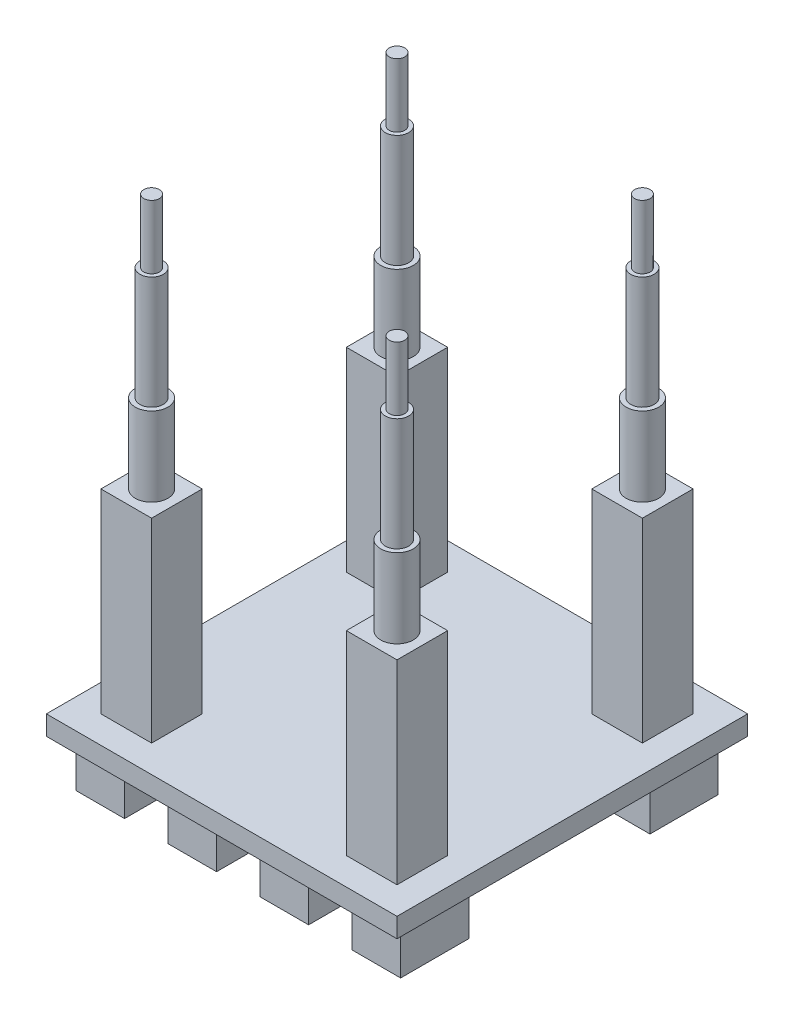
SolidWorks part; units mm, degrees
ref_plane "Front Plane" through (0, 0, 0) normal (0, 0, 1) x (1, 0, 0)
ref_plane "Top Plane" through (0, 0, 0) normal (0, 1, 0) x (1, 0, 0)
ref_plane "Right Plane" through (0, 0, 0) normal (1, 0, 0) x (0, 0, -1)
sketch "Sketch1" plane through (0, 0, 0) normal (0, 1, 0) x (1, 0, 0)
  line L1 (-22.86, 22.86) -> (22.86, 22.86)
  line L2 (-22.86, 22.86) -> (-22.86, -22.86)
  line L3 (-22.86, -22.86) -> (22.86, -22.86)
  line L4 (22.86, 22.86) -> (22.86, -22.86)
extrude "Boss-Extrude1" add sketch "Sketch1" along normal blind 2.54
sketch "Sketch2" plane through (0, 2.54, 0) normal (0, 1, 0) x (1, 0, 0)
  line L0 (0, 22.86) -> (0, -22.86) construction
  line L1 (22.86, 22.86) -> (-22.86, 22.86) construction
  line L2 (-22.86, -22.86) -> (22.86, -22.86) construction
  line L3 (-22.86, 0) -> (22.86, 0) construction
  line L4 (-22.86, 22.86) -> (-22.86, -22.86) construction
  line L5 (22.86, -22.86) -> (22.86, 22.86) construction
  line L6 (19.302, 19.302) -> (12.698, 19.302)
  line L7 (-19.302, 19.302) -> (-12.698, 19.302)
  line L8 (-19.302, 19.302) -> (-19.302, 12.698)
  line L9 (-19.302, 12.698) -> (-12.698, 12.698)
  line L10 (-12.698, 19.302) -> (-12.698, 12.698)
  line L11 (-19.302, 19.302) -> (-12.698, 12.698) construction
  line L12 (-19.302, 12.698) -> (-12.698, 19.302) construction
  line L13 (19.302, 19.302) -> (19.302, 12.698)
  line L14 (19.302, 12.698) -> (12.698, 12.698)
  line L15 (12.698, 19.302) -> (12.698, 12.698)
  line L16 (-19.302, -12.698) -> (-12.698, -12.698)
  line L17 (-19.302, -19.302) -> (-19.302, -12.698)
  line L18 (-19.302, -19.302) -> (-12.698, -19.302)
  line L19 (-12.698, -19.302) -> (-12.698, -12.698)
  line L20 (12.698, -19.302) -> (12.698, -12.698)
  line L21 (19.302, -12.698) -> (12.698, -12.698)
  line L22 (19.302, -19.302) -> (19.302, -12.698)
  line L23 (19.302, -19.302) -> (12.698, -19.302)
  point P1 (-16, 16)
  dimension "D1" = 6.604
extrude "Boss-Extrude2" add sketch "Sketch2" along normal blind 25.4
sketch "Sketch5" plane through (0, 27.94, 0) normal (0, 1, 0) x (1, 0, 0)
  line L0 (0, 22.86) -> (0, -22.86) construction
  line L2 (22.86, 0) -> (-22.86, 0) construction
  line L3 (-22.86, 0) -> (22.86, 0) construction
  line L4 (-22.86, 22.86) -> (-22.86, -22.86) construction
  line L5 (0, 22.86) -> (0, -22.86) construction
  circle A0 centre (-16, 16) radius 2.125
  circle A1 centre (16, 16) radius 2.125
  circle A2 centre (-16, -16) radius 2.125
  circle A3 centre (16, -16) radius 2.125
  dimension "D1" = 4.25
extrude "Boss-Extrude5" add sketch "Sketch5" along normal blind 10.3
sketch "Sketch8" plane through (0, 38.24, 0) normal (0, 1, 0) x (1, 0, 0)
  line L0 (-16, 0) -> (16, 0) construction
  line L1 (0, -16) -> (0, 16) construction
  circle A0 centre (16, 16) radius 1.525
  circle A1 centre (-16, 16) radius 1.525
  circle A2 centre (-16, -16) radius 1.525
  circle A3 centre (16, -16) radius 1.525
  point P6 (0, 0)
  point P10 (0, 0)
extrude "Boss-Extrude8" add sketch "Sketch8" along normal blind 14.7
sketch "Sketch9" plane through (0, 52.94, 0) normal (0, 1, 0) x (1, 0, 0)
  line L0 (-16, 0) -> (16, 0) construction
  line L1 (0, -16) -> (0, 16) construction
  circle A0 centre (16, 16) radius 1.015
  circle A1 centre (-16, 16) radius 1.015
  circle A2 centre (-16, -16) radius 1.015
  circle A3 centre (16, -16) radius 1.015
  point P7 (0, 0)
  point P11 (0, 0)
extrude "Boss-Extrude9" add sketch "Sketch9" along normal blind 8.3
sketch "Sketch7" plane through (0, 0, 0) normal (0, -1, 0) x (1, 0, 0)
  line L0 (0, 22.86) -> (0, -22.86) construction
  line L1 (-9.175, 20.701) -> (-2.825, 20.701)
  line L2 (-9.175, 20.701) -> (-9.175, 11.811)
  line L3 (-9.175, 11.811) -> (-2.825, 11.811)
  line L4 (-2.825, 20.701) -> (-2.825, 11.811)
  line L5 (-9.175, 20.701) -> (-2.825, 11.811) construction
  line L6 (-9.175, 11.811) -> (-2.825, 20.701) construction
  line L7 (-22.86, 22.86) -> (22.86, 22.86) construction
  line L8 (22.86, -22.86) -> (-22.86, -22.86) construction
  line L9 (-22.86, 0) -> (22.86, 0) construction
  line L10 (-22.86, -22.86) -> (-22.86, 22.86) construction
  line L11 (22.86, 22.86) -> (22.86, -22.86) construction
  line L16 (-6, 16.256) -> (0, 16.256) construction
  line L17 (-6, 16.256) -> (-12, 16.256) construction
  line L18 (-12, 22.86) -> (-12, -22.86) construction
  line L19 (-14.825, 11.811) -> (-21.175, 11.811)
  line L20 (-21.175, 20.701) -> (-21.175, 11.811)
  line L21 (-14.825, 20.701) -> (-14.825, 11.811)
  line L22 (-14.825, 20.701) -> (-21.175, 20.701)
  line L23 (9.175, 20.701) -> (9.175, 11.811)
  line L24 (9.175, 20.701) -> (2.825, 20.701)
  line L25 (2.825, 20.701) -> (2.825, 11.811)
  line L26 (9.175, 11.811) -> (2.825, 11.811)
  line L27 (14.825, 11.811) -> (21.175, 11.811)
  line L28 (14.825, 20.701) -> (14.825, 11.811)
  line L29 (14.825, 20.701) -> (21.175, 20.701)
  line L30 (21.175, 20.701) -> (21.175, 11.811)
  line L31 (-9.175, -11.811) -> (-2.825, -11.811)
  line L32 (-2.825, -20.701) -> (-2.825, -11.811)
  line L33 (-9.175, -20.701) -> (-9.175, -11.811)
  line L34 (-9.175, -20.701) -> (-2.825, -20.701)
  line L35 (-14.825, -20.701) -> (-21.175, -20.701)
  line L36 (-14.825, -20.701) -> (-14.825, -11.811)
  line L37 (-21.175, -20.701) -> (-21.175, -11.811)
  line L38 (-14.825, -11.811) -> (-21.175, -11.811)
  line L39 (21.175, -20.701) -> (21.175, -11.811)
  line L40 (14.825, -20.701) -> (21.175, -20.701)
  line L41 (14.825, -20.701) -> (14.825, -11.811)
  line L42 (14.825, -11.811) -> (21.175, -11.811)
  line L43 (9.175, -11.811) -> (2.825, -11.811)
  line L44 (2.825, -20.701) -> (2.825, -11.811)
  line L45 (9.175, -20.701) -> (2.825, -20.701)
  line L46 (9.175, -20.701) -> (9.175, -11.811)
  point P0 (-6, 16.256)
  dimension "D1" = 6.35
  dimension "D2" = 8.89
  dimension "D3" = 6
extrude "Boss-Extrude7" add sketch "Sketch7" along normal blind 6.35
